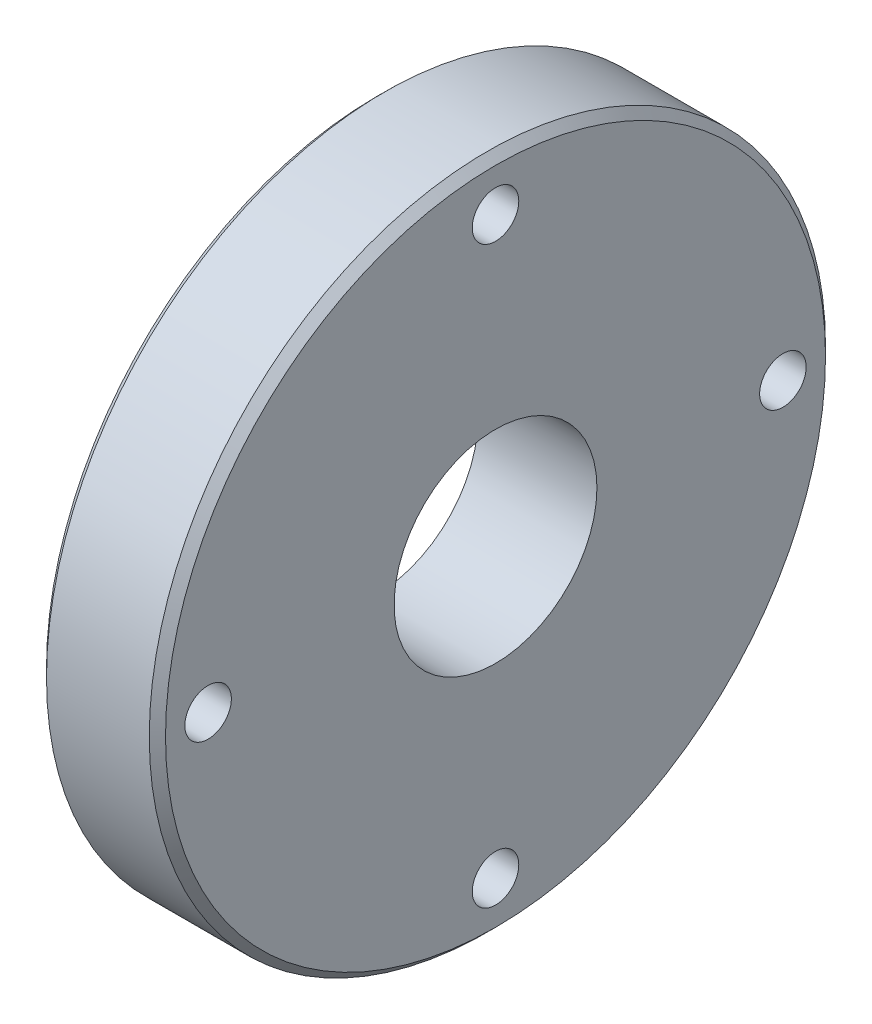
SolidWorks part; units mm, degrees
ref_plane "Front Plane" through (0, 0, 0) normal (1, 0, 0) x (0, 1, 0)
ref_plane "Top Plane" through (0, 0, 0) normal (0, 0, 1) x (0, 1, 0)
ref_plane "Right Plane" through (0, 0, 0) normal (0, 1, 0) x (-1, 0, 0)
sketch "Sketch1" plane through (0, 0, 0) normal (1, 0, 0) x (0, 1, 0)
  circle A0 centre (0, 0) radius 63.5
extrude "Boss-Extrude1" add sketch "Sketch1" along normal blind 22.352
sketch "Sketch2" plane through (0, 0, 0) normal (1, 0, 0) x (0, 1, 0)
  circle A0 centre (0, 0) radius 19.05
extrude "Cut-Extrude2" cut sketch "Sketch2" along normal through all
sketch "Sketch3" plane through (0, 0, 0) normal (1, 0, 0) x (0, 1, 0)
  circle A0 centre (53.975, 0) radius 4.3688
  circle A1 centre (0, 53.975) radius 4.3688
  circle A2 centre (-53.975, 0) radius 4.3688
  circle A3 centre (0, -53.975) radius 4.3688
extrude "Cut-Extrude4" cut sketch "Sketch3" along normal through all
sketch "Sketch4" plane through (0, 0, 0) normal (1, 0, 0) x (0, 1, 0)
  circle A0 centre (53.975, 0) radius 6.7437
  circle A1 centre (0, 53.975) radius 6.7437
  circle A2 centre (-53.975, 0) radius 6.7437
  circle A3 centre (0, -53.975) radius 6.7437
extrude "Cut-Extrude5" cut sketch "Sketch4" along normal blind 9.652
chamfer "Chamfer1" distance 1.524 angle 45 2 edges at (22.352, 0, -63.5) (0, 0, -63.5)
